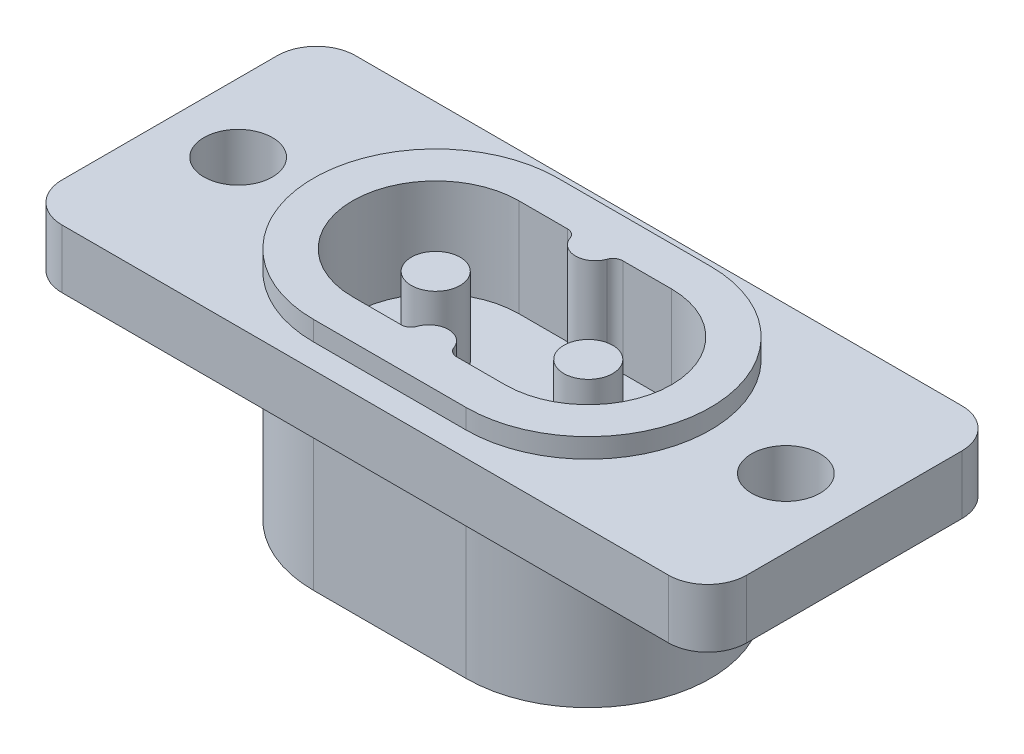
SolidWorks part; units mm, degrees
ref_plane "前视基准面" through (0, 0, 0) normal (0, 0, 1) x (1, 0, 0)
ref_plane "上视基准面" through (0, 0, 0) normal (0, 1, 0) x (1, 0, 0)
ref_plane "右视基准面" through (0, 0, 0) normal (1, 0, 0) x (0, 0, -1)
sketch "草图1" plane through (0, 0, 0) normal (0, 1, 0) x (1, 0, 0)
  line L1 (-17.5, 7.5) -> (17.5, 7.5)
  line L2 (-17.5, 7.5) -> (-17.5, -7.5)
  line L3 (-17.5, -7.5) -> (17.5, -7.5)
  line L4 (17.5, 7.5) -> (17.5, -7.5)
  line L5 (-17.5, 7.5) -> (17.5, -7.5) construction
  line L6 (-17.5, -7.5) -> (17.5, 7.5) construction
  point P0 (0, 0)
  dimension "D1" = 35
  dimension "D2" = 15
extrude "凸台-拉伸1" add sketch "草图1" along normal blind 3
sketch "草图2" plane through (0, 3, 0) normal (0, 1, 0) x (1, 0, 0)
  line L2 (-3.9, 0) -> (3.9, 0) construction
  line L3 (-3.9, 6.25) -> (3.9, 6.25)
  line L4 (-3.9, -6.25) -> (3.9, -6.25)
  arc A0 (-3.9, 6.25) -> (-3.9, -6.25) centre (-3.9, 0) ccw
  arc A1 (3.9, -6.25) -> (3.9, 6.25) centre (3.9, 0) ccw
  point P5 (0, 0)
  point P10 (-10.15, 0)
  point P11 (10.15, 0)
  dimension "D2" = 12.5
  dimension "D1" = 20.3
extrude "凸台-拉伸2" add sketch "草图2" along normal blind 1 and the other way blind 11
sketch "草图3" plane through (0, 3, 0) normal (0, 1, 0) x (1, 0, 0)
  line L0 (-17.5, 0) -> (17.5, 0) construction
  line L1 (-17.5, 7.5) -> (-17.5, -7.5) construction
  line L2 (17.5, -7.5) -> (17.5, 7.5) construction
  line L3 (0, 0) -> (0, 6.25) construction
  line L4 (3.9, 6.25) -> (-3.9, 6.25) construction
  circle A0 centre (-14, 0) radius 1.75
  circle A1 centre (14, 0) radius 1.75
  dimension "D2" = 3.5
  dimension "D1" = 28
extrude "切除-拉伸1" cut sketch "草图3" against normal through all
sketch "草图5" plane through (0, 4, 0) normal (0, 1, 0) x (1, 0, 0)
  line L4 (-1.4142, 4.25) -> (-3.9, 4.25)
  line L5 (0, 0) -> (3.9, 0) construction
  line L6 (-3.9, -4.25) -> (3.9, -4.25)
  line L7 (3.9, 4.25) -> (-3.9, 4.25)
  line L8 (-3.9, -4.25) -> (-1.4142, -4.25)
  line L9 (3.9, 4.25) -> (1.4142, 4.25)
  line L10 (1.4142, -4.25) -> (3.9, -4.25)
  arc A6 (-0.9428, 3.9167) -> (0.9428, 3.9167) centre (0, 4.25) ccw
  arc A7 (-0.9428, -3.9167) -> (0.9428, -3.9167) centre (0, -4.25) cw
  arc A8 (3.9, -4.25) -> (3.9, 4.25) centre (3.9, 0) ccw
  arc A9 (-3.9, 4.25) -> (-3.9, -4.25) centre (-3.9, 0) ccw
  arc A10 (3.9, -4.25) -> (3.9, 4.25) centre (3.9, 0) ccw
  arc A11 (-3.9, 4.25) -> (-3.9, -4.25) centre (-3.9, 0) ccw
  arc A12 (-0.9428, -3.9167) -> (-1.4142, -4.25) centre (-1.4142, -3.75) cw
  arc A13 (-0.9428, 3.9167) -> (-1.4142, 4.25) centre (-1.4142, 3.75) ccw
  arc A14 (0.9428, -3.9167) -> (1.4142, -4.25) centre (1.4142, -3.75) ccw
  arc A15 (0.9428, 3.9167) -> (1.4142, 4.25) centre (1.4142, 3.75) cw
  dimension "D2" = 1
  dimension "D3" = 0.5
  dimension "D4" = 0.5
  dimension "D1" = 2
extrude "切除-拉伸2" cut sketch "草图5" against normal blind 5
sketch "草图6" plane through (0, -1, 0) normal (0, 1, 0) x (1, 0, 0)
  line L0 (-3.9, 0) -> (3.9, 0) construction
  circle A0 centre (-3.9, 0) radius 1.25
  circle A1 centre (3.9, 0) radius 1.25
  dimension "D1" = 2.5
extrude "凸台-拉伸3" add sketch "草图6" along normal blind 4
fillet "圆角1" radius 2 4 edges at (-17.5, 1.5, 7.5) (17.5, 1.5, 7.5) (17.5, 1.5, -7.5) (-17.5, 1.5, -7.5)
sketch "草图7" plane through (0, -8, 0) normal (0, -1, 0) x (1, 0, 0)
  line L1 (-4.7209, 1.8845) -> (-3.6168, 1.8845)
  line L2 (-4.7209, 1.8845) -> (-4.7209, -1.5419)
  line L3 (-4.7209, -1.5419) -> (-3.6168, -1.5419)
  line L4 (-3.6168, 1.8845) -> (-3.6168, -1.5419)
  line L5 (3.2361, 1.8845) -> (4.3021, 1.8845)
  line L6 (3.2361, 1.8845) -> (3.2361, -1.5419)
  line L7 (3.2361, -1.5419) -> (4.3021, -1.5419)
  line L8 (4.3021, 1.8845) -> (4.3021, -1.5419)
extrude "凸台-拉伸4" add sketch "草图7" along normal blind 3
